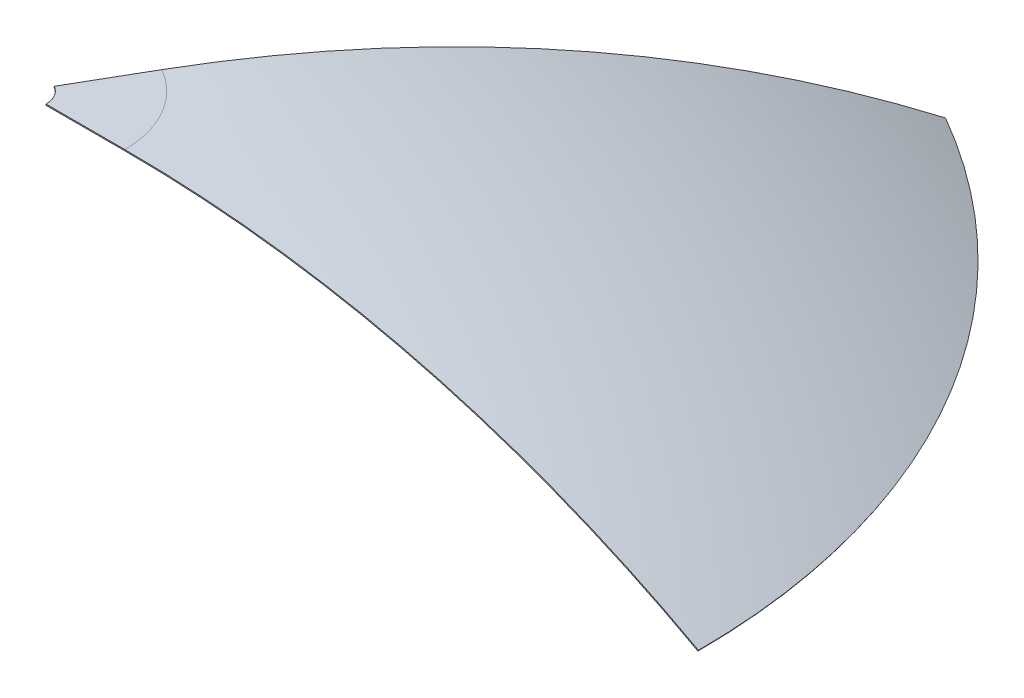
SolidWorks part; units mm, degrees
ref_plane "Front Plane" through (0, 0, 0) normal (0, 0, 1) x (1, 0, 0)
ref_plane "Top Plane" through (0, 0, 0) normal (0, 1, 0) x (1, 0, 0)
ref_plane "Right Plane" through (0, 0, 0) normal (1, 0, 0) x (0, 0, -1)
sketch "Sketch1" plane through (0, 0, 0) normal (0, 0, 1) x (1, 0, 0)
  line L0 (10, -0.5) -> (45, -0.5)
  line L1 (10, -0.5) -> (-10, -0.5) construction
  line L2 (10, -0.5) -> (-10, -0.5) construction
  line L4 (45, -0.5) -> (-45, -0.5) construction
  line L5 (10, 0) -> (45, 0)
  line L6 (299.7402, -65.211) -> (299.5, -65.6495)
  line L7 (10, -0.5) -> (10, 0)
  line L8 (0, -1000) -> (0, 49000) construction
  arc A0 (299.5, -65.6495) -> (46.0019, -0.5009) centre (45, -530.1639) ccw construction
  arc A1 (299.5, -65.6495) -> (46.0019, -0.5009) centre (45, -530.1639) ccw
  arc A2 (46.0019, -0.5009) -> (45, -0.5) centre (45, -530.1639) ccw
  arc A3 (46.0028, -0.0009) -> (45, 0) centre (45, -530.1639) ccw
  arc A4 (299.7402, -65.211) -> (46.0028, -0.0009) centre (45, -530.1639) ccw
  dimension "D1" = 0.5
revolve "Revolve1" add sketch "Sketch1" angle 60 about L8
